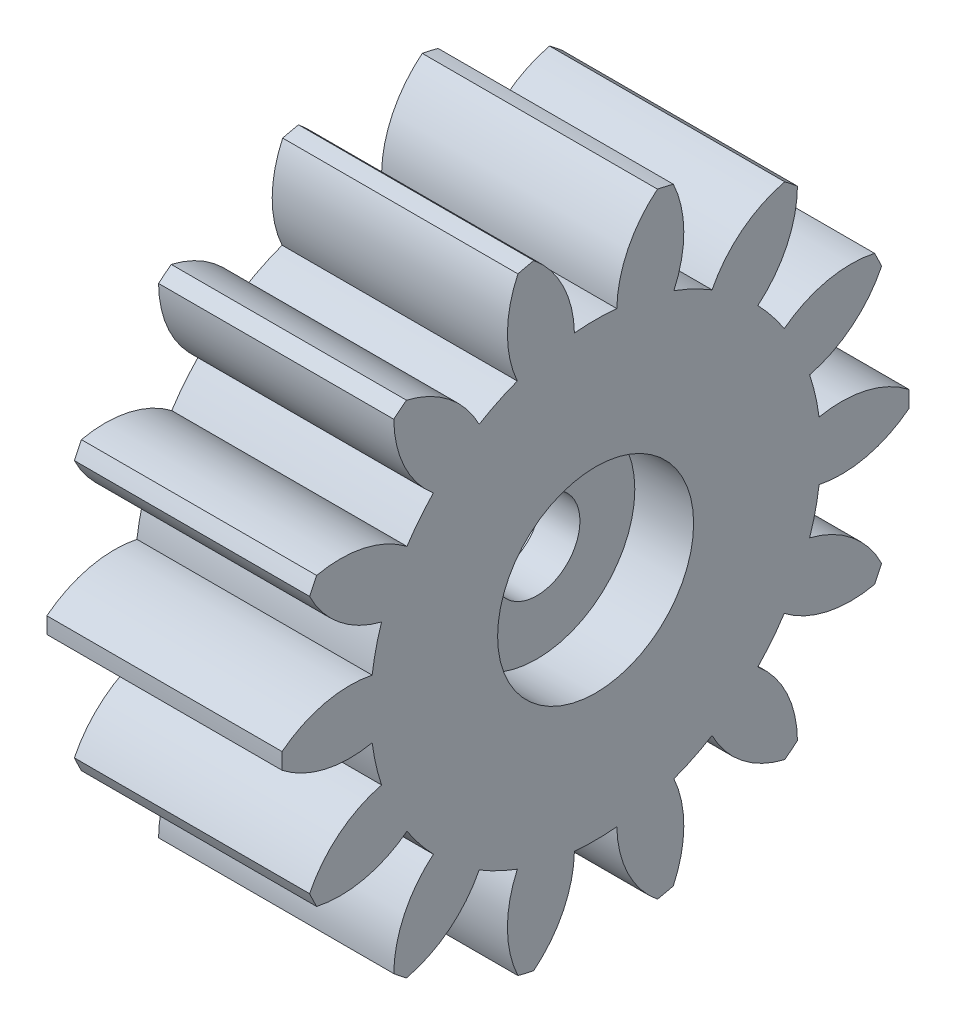
SolidWorks part; units mm, degrees
ref_plane "Plane1" through (0, 0, 0) normal (0, 0, 1) x (1, 0, 0)
ref_plane "Plane2" through (0, 0, 0) normal (0, 1, 0) x (1, 0, 0)
ref_plane "Plane3" through (0, 0, 0) normal (1, 0, 0) x (0, 0, -1)
other "Configuration Table"
sketch "HoldingSke" plane through (0, 0, 0) normal (0, 1, 0) x (1, 0, 0)
  line L0 (0, 0) -> (0.9703, -0.2419)
  line L1 (-15, 0) -> (100, 0) construction
  line L2 (0, 0) -> (-2.1039, 2.3779)
  line L3 (0, 0) -> (-11.863, 4.5341)
  line L4 (0, 0) -> (8.3795, 2.0892)
  line L5 (0, 0) -> (-46.8476, -17.4728)
  line L6 (0, 0) -> (-4.9738, -3.3558)
  line L7 (-2.1039, 2.3779) -> (8.6586, 51.2059)
  line L8 (-76.2, 54.61) -> (-76.1, 54.61)
  line L9 (-71.009, 38.7566) -> (-53.1078, 45.2721)
  line L10 (-76.2, 71.12) -> (104.1128, 71.12)
  line L11 (0, 0) -> (-6, 0)
  line L12 (-76.2, 101.6) -> (-76.162, 101.6)
  line L13 (24.9733, 27.94) -> (52.9518, 28.4284)
  line L14 (24.9733, 27.94) -> (24.9743, 27.94)
  line L15 (24.9733, 27.94) -> (100.4006, 29.5858)
  line L16 (-63.627, -1) -> (-12.827, -1)
  circle A0 centre (0, 0) radius 0.4
  circle A1 centre (0, 0) radius 5.749
  circle A2 centre (0, 0) radius 37.5
  circle A3 centre (0, 0) radius 0.4
  dimension "MHD" = 11.498
  dimension "Hub_dia" = 75
  dimension "Bore" = 0.8
  dimension "MBD" = 0.8
  dimension "Num_teeth" = 14
  dimension "Pitch" = 1
  dimension "Overall_len" = 50
  dimension "Show_teeth" = 14
  dimension "Thickness" = 6
  dimension "OAL" = 50.0001
  dimension "T_dim" = 0.1
  dimension "Ap" = 20
  dimension "H" = 19.05
  dimension "Pitch_radius" = 180.3128
  dimension "Width" = 6
  dimension "Backlash" = 0.038
  dimension "Addendum_fac" = 1
  dimension "Dedendum_fac" = 1.25
  dimension "Clearance_fac" = 0.25
  dimension "Dedendum_add" = 0.001
  dimension "Module" = 1
sketch "BasProSke" plane through (0, 0, 0) normal (0, 1, 0) x (1, 0, 0)
  line L0 (-10, 0) -> (60, 0) construction
  line L1 (0, 0) -> (0, 8)
  line L2 (0, 0) -> (6, 0)
  line L3 (6, 0) -> (6, 8)
  line L4 (6, 8) -> (0, 8)
  dimension "Thickness" = 6
  dimension "Diameter" = 16
revolve "Base-Revolve" add sketch "BasProSke" angle 360 about L0
sketch "TooCutSke" plane through (0, 0, 0) normal (1, 0, 0) x (0, 0, -1)
  line L1 (0, 0) -> (0, 107) construction
  line L2 (0, 0) -> (-0.8502, 6.9482) construction
  line L3 (0, 0) -> (-3.0989, 13.5772) construction
  line L4 (-0.8502, 6.9482) -> (-1.5494, 6.7886) construction
  arc A0 (0.5404, 5.7235) -> (-0.5404, 5.7235) centre (0, 0) ccw
  arc A1 (1.6036, 7.8636) -> (-1.6036, 7.8636) centre (0, 0) ccw
  circle A2 centre (0, 0) radius 7 construction
  circle A3 centre (0, 0) radius 6.5778 construction
  arc A4 (-0.5404, 5.7235) -> (-1.6036, 7.8636) centre (-3.3398, 5.6669) ccw
  arc A5 (1.6036, 7.8636) -> (0.5404, 5.7235) centre (3.3398, 5.6669) ccw
  dimension "Root_dia" = 11.498
  dimension "Overcut_dia" = 16.0508
  dimension "Pitch_dia" = 14
  dimension "Base_dia" = 13.1557
  dimension "Flank_rad" = 2.8
  dimension "Half_ang" = 12.857
  dimension "Half_CT" = 0.7173
extrude "ToothCut" cut sketch "TooCutSke" along normal through all
fillet "Breaks" [suppressed] radius 0.02
fillet "RootFillets" [suppressed] radius 0.251
pattern_circular "TeethCuts" count 14 every 25.714 about axis through (-10, 0, 0) along (1, 0, 0) of "ToothCut", "RootFillets", "Breaks"
sketch "HubNeaOneSke" plane through (0, 0, 0) normal (-1, 0, 0) x (0, 0, 1)
  circle A0 centre (0, 0) radius 5.749
  dimension "Diameter" = 11.498
extrude "HubNearOne" [suppressed] add sketch "HubNeaOneSke" along normal blind 44.0001
sketch "HubNeaBotSke" plane through (0, 0, 0) normal (-1, 0, 0) x (0, 0, 1)
  circle A0 centre (0, 0) radius 5.749
  dimension "Diameter" = 11.498
extrude "HubNearBoth" [suppressed] add sketch "HubNeaBotSke" along normal blind 22
ref_plane "FarPln" through (6, 0, 0) normal (1, 0, 0) x (0, 0, -1)
sketch "HubFarSke" plane through (6, 0, 0) normal (1, 0, 0) x (0, 0, -1)
  circle A0 centre (0, 0) radius 5.749
  dimension "Diameter" = 11.498
extrude "HubFar" [suppressed] add sketch "HubFarSke" along normal blind 22
sketch "BorSke" plane through (0, 0, 0) normal (1, 0, 0) x (0, 0, -1)
  circle A0 centre (0, 0) radius 0.4
  dimension "Diameter" = 0.8
extrude "Bore" cut sketch "BorSke" along normal mid plane 100.0001
sketch "KeySke" plane through (0, 0, 0) normal (1, 0, 0) x (0, 0, -1)
  line L0 (-0.05, 0) -> (-0.05, 0.5)
  line L1 (-0.05, 0.5) -> (0.05, 0.5)
  line L2 (0.05, 0.5) -> (0.05, 0)
  line L3 (0, 0) -> (0, 34) construction
  line L4 (-0.05, 0) -> (0.05, 0)
  dimension "Offset" = 0.5
  dimension "Width" = 0.1
extrude "Keyway" [suppressed] cut sketch "KeySke" along normal mid plane 100.0001
pattern_circular "Keyway2" [suppressed] count 2 every 90 about axis through (-10, 0, 0) along (1, 0, 0)
sketch "Sketch1" plane through (6, 0, 0) normal (1, 0, 0) x (0, 0, -1)
  circle A0 centre (0, 0) radius 2.5
  dimension "D1" = 5
extrude "Cut-Extrude1" cut sketch "Sketch1" against normal blind 1.5
sketch "Sketch2" plane through (0, 0, 0) normal (-1, 0, 0) x (0, 0, 1)
  circle A0 centre (0, 0) radius 2.5
  dimension "D1" = 5
extrude "Cut-Extrude2" cut sketch "Sketch2" against normal blind 3.5
sketch "Sketch3" plane through (4.5, 0, 0) normal (1, 0, 0) x (0, 0, -1)
  circle A0 centre (0, 0) radius 1.1
  dimension "D1" = 2.2
extrude "Cut-Extrude3" cut sketch "Sketch3" against normal blind 2.2
equation "' \"Module@HoldingSke\" = 6.35"
equation "' \"Num_teeth@HoldingSke\" = 12"
equation "' \"Ap@HoldingSke\" =  20"
equation "' \"Ap@HoldingSke\" = 20"
equation "' \"Width@HoldingSke\" = 0.5 * 25.4"
equation "' \"Hub_dia@HoldingSke\"= 1 * 25.4"
equation "' \"Hub_dia@HoldingSke\" = 1 * 25.4"
equation "' \"Overall_len@HoldingSke\" = 1.0 * 25.4"
equation "' \"Bore@HoldingSke\" = 0.75 * 25.4"
equation "' \"T_dim@HoldingSke\" = 0.1 * 25.4"
equation "' \"Width@KeySke\" = 0.25 * 25.4"
equation "' \"Show_teeth@HoldingSke\" = 13"
equation "' \"Backlash@HoldingSke\" = 0.009 * 25.4"
equation "' \"Addendum_fac@HoldingSke\" = 1.0"
equation "' \"Dedendum_fac@HoldingSke\" = 1.25"
equation "' \"Dedendum_add@HoldingSke\" = 0.00005 * 25.4"
equation "' \"Clearance_fac@HoldingSke\" = 0.25"
equation "\"Pitch@HoldingSke\" = 1 / \"Module@HoldingSke\""
equation "\"Overcut_dia@TooCutSke\" = (\"Num_teeth@HoldingSke\" + 2 * \"Addendum_fac@HoldingSke\") / \"Pitch@HoldingSke\" + 0.002 * 25.4"
equation "\"Pitch_dia@TooCutSke\" = \"Num_teeth@HoldingSke\" / \"Pitch@HoldingSke\""
equation "\"Base_dia@TooCutSke\" = \"Num_teeth@HoldingSke\" / \"Pitch@HoldingSke\" * cos((\"Ap@HoldingSke\"  * 3.14159265 / 180))"
equation "\"Root_dia@TooCutSke\" = (\"Num_teeth@HoldingSke\" + 2) / \"Pitch@HoldingSke\" - 2 * (\"Addendum_fac@HoldingSke\" + \"Dedendum_fac@HoldingSke\") / \"Pitch@HoldingSke\" - \"Dedendum_add@HoldingSke\" * 2"
equation "\"Half_ang@TooCutSke\" = 180 / \"Num_teeth@HoldingSke\""
equation "\"Half_CT@TooCutSke\" = \"Num_teeth@HoldingSke\" / \"Pitch@HoldingSke\" * sin((3.14159265 / 2 / \"Num_teeth@HoldingSke\")) / 2 - 7 * \"Backlash@HoldingSke\" / 4"
equation "\"Flank_rad@TooCutSke\" = \"Num_teeth@HoldingSke\" / \"Pitch@HoldingSke\" / 5"
equation "\"Radius@RootFillets\" = \"Clearance_fac@HoldingSke\" / \"Pitch@HoldingSke\" + \"Dedendum_add@HoldingSke\""
equation "\"Break_rad@Breaks\" = 0.02 / \"Pitch@HoldingSke\""
equation "\"Thickness@HoldingSke\" = \"Width@HoldingSke\""
equation "\"OAL@HoldingSke\" = \"Thickness@HoldingSke\""
equation "\"MHD@HoldingSke\" = (\"Num_teeth@HoldingSke\" + 2) / \"Pitch@HoldingSke\" - 2 * (\"Addendum_fac@HoldingSke\" + \"Dedendum_fac@HoldingSke\")  / \"Pitch@HoldingSke\" - \"Dedendum_add@HoldingSke\" * 2"
equation "\"MBD@HoldingSke\" = (\"Num_teeth@HoldingSke\" + 2) / \"Pitch@HoldingSke\" - 2 * (\"Addendum_fac@HoldingSke\" + \"Dedendum_fac@HoldingSke\")  / \"Pitch@HoldingSke\" - \"Dedendum_add@HoldingSke\" * 2 - 0.002 * 25.4"
equation "\"MHD@HoldingSke\" = ((sgn( \"MHD@HoldingSke\" - \"Hub_dia@HoldingSke\" )-1)*( \"MHD@HoldingSke\" - \"Hub_dia@HoldingSke\" ))/-2+ \"Hub_dia@HoldingSke\""
equation "\"MBD@HoldingSke\" = ((sgn( \"MBD@HoldingSke\" - \"Bore@HoldingSke\" )-1)*( \"MBD@HoldingSke\" - \"Bore@HoldingSke\" ))/-2+ \"Bore@HoldingSke\""
equation "\"OAL@HoldingSke\" = ((sgn( \"OAL@HoldingSke\" - \"Overall_len@HoldingSke\" )+1)*( \"OAL@HoldingSke\" - \"Overall_len@HoldingSke\" ))/2 + \"Overall_len@HoldingSke\" + 0.000002 * 25.4"
equation "\"Num_teeth@TeethCuts\" = int( \"Show_teeth@HoldingSke\" ) + 1"
equation "\"Num_teeth@TeethCuts\" = ((sgn( \"Num_teeth@TeethCuts\" - \"Num_teeth@HoldingSke\" )-1)*( \"Num_teeth@TeethCuts\" - \"Num_teeth@HoldingSke\" ))/-2+ \"Num_teeth@HoldingSke\""
equation "\"Num_teeth@TeethCuts\" = ((sgn( \"Num_teeth@TeethCuts\" - 2.0)+1)*( \"Num_teeth@TeethCuts\" - 2.0))/2 +2.0"
equation "\"Angle@TeethCuts\" = 360.0 / \"Num_teeth@HoldingSke\""
equation "\"Diameter@BasProSke\" = (\"Num_teeth@HoldingSke\" + 2 * \"Addendum_fac@HoldingSke\") / \"Pitch@HoldingSke\""
equation "\"Thickness@BasProSke\"  = \"Thickness@HoldingSke\""
equation "' \"Fillet_rad@BasProSke\" =  \"Thickness@HoldingSke\" * 0.05"
equation "' \"Fillet_rad@BasProSke\" = \"Thickness@HoldingSke\" * 0.05"
equation "\"MHD@HoldingSke\" = ((sgn( \"MHD@HoldingSke\" - \"Root_dia@TooCutSke\" )-1)*( \"MHD@HoldingSke\" - \"Root_dia@TooCutSke\" ))/-2+ \"Root_dia@TooCutSke\""
equation "\"Diameter@HubNeaOneSke\" = \"MHD@HoldingSke\""
equation "\"Length@HubNearOne\" = \"OAL@HoldingSke\" - \"Thickness@BasProSke\""
equation "\"Diameter@HubNeaBotSke\" = \"MHD@HoldingSke\""
equation "\"Length@HubNearBoth\" = ( \"OAL@HoldingSke\" - \"Thickness@BasProSke\" ) / 2.0"
equation "\"Thickness@FarPln\" = \"Thickness@BasProSke\""
equation "\"Diameter@HubFarSke\" = \"MHD@HoldingSke\""
equation "\"Length@HubFar\" = ( \"OAL@HoldingSke\" - \"Thickness@BasProSke\" ) / 2.0"
equation "\"Diameter@BorSke\" = \"MBD@HoldingSke\""
equation "\"D1@Bore\" = \"OAL@HoldingSke\" * 2.0"
equation "\"D1@Keyway\" = \"OAL@HoldingSke\" * 2.0"
equation "\"Offset@KeySke\" = \"T_dim@HoldingSke\" + \"MBD@HoldingSke\" / 2.0"
